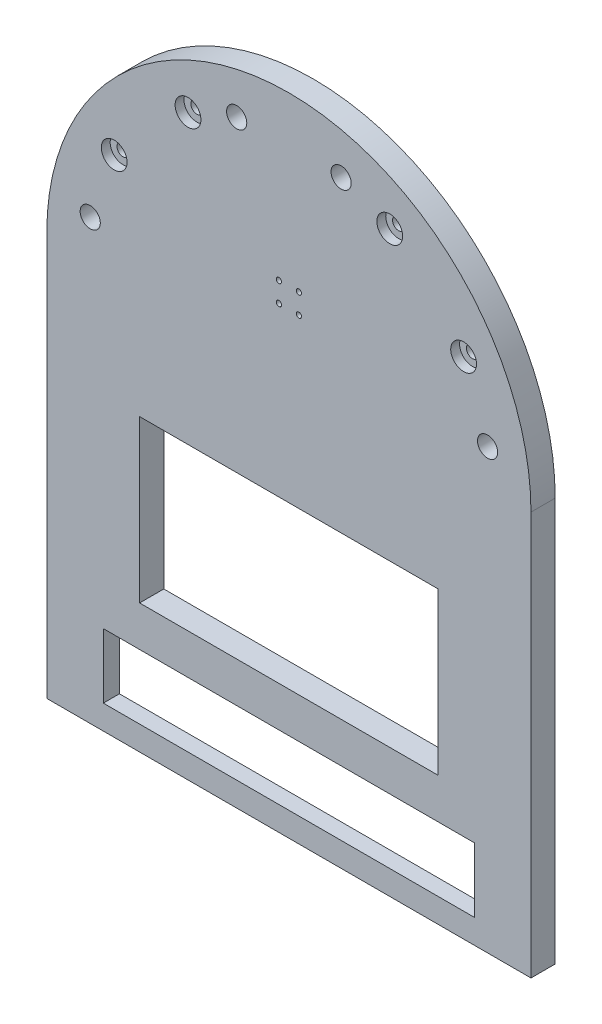
SolidWorks part; units mm, degrees
ref_plane "前视基准面" through (0, 0, 0) normal (0, 0, 1) x (1, 0, 0)
ref_plane "上视基准面" through (0, 0, 0) normal (0, 1, 0) x (1, 0, 0)
ref_plane "右视基准面" through (0, 0, 0) normal (1, 0, 0) x (0, 0, -1)
sketch "草图1" plane through (0, 0, 0) normal (0, 0, 1) x (1, 0, 0)
  line L0 (0, 0) -> (0, 283.2621) construction
  line L1 (0, 0) -> (-125, 216.5064) construction
  line L2 (0, 0) -> (-216.5064, 125) construction
  line L3 (-300, 0) -> (-300, -500)
  line L4 (-300, -500) -> (300, -500)
  line L5 (300, -500) -> (300, 0)
  arc A0 (300, 0) -> (-300, 0) centre (0, 0) ccw
  circle A1 centre (0, 0) radius 250 construction
  circle A2 centre (-216.5064, 125) radius 16
  circle A3 centre (-125, 216.5064) radius 16
  circle A4 centre (125, 216.5064) radius 16
  circle A5 centre (216.5064, 125) radius 16
  dimension "D1" = 300
  dimension "D2" = 500
  dimension "D5" = 32
  dimension "D6" = 32
  dimension "D7" = 500
  dimension "D3" = 30
  dimension "D4" = 30
extrude "凸台-拉伸1" add sketch "草图1" along normal blind 30
sketch "草图2" plane through (0, 0, 0) normal (0, 0, -1) x (-1, 0, 0)
  line L0 (0, 0) -> (0, 105.4108) construction
  circle A0 centre (-216.5064, 125) radius 18.5
  circle A1 centre (-125, 216.5064) radius 18.5
  circle A2 centre (-216.5064, 125) radius 22.5
  circle A3 centre (-125, 216.5064) radius 22.5
  circle A4 centre (216.5064, 125) radius 22.5
  circle A5 centre (216.5064, 125) radius 18.5
  circle A6 centre (125, 216.5064) radius 22.5
  circle A7 centre (125, 216.5064) radius 18.5
  dimension "D1" = 45
  dimension "D2" = 45
  dimension "D3" = 37
  dimension "D4" = 37
sketch "草图5" plane through (0, 0, 30) normal (0, 0, 1) x (1, 0, 0)
  line L1 (-185, -140) -> (185, -140)
  line L2 (-185, -140) -> (-185, -340)
  line L3 (-185, -340) -> (185, -340)
  line L4 (185, -140) -> (185, -340)
  line L5 (0, -340) -> (0, -140) construction
  line L6 (-185, -240) -> (185, -240) construction
  point P0 (0, -240)
  dimension "D1" = 200
  dimension "D2" = 370
  dimension "D3" = 240
extrude "切除-拉伸3" cut sketch "草图5" against normal through all
sketch "草图6" plane through (0, 0, 30) normal (0, 0, 1) x (1, 0, 0)
  line L1 (-230, -390) -> (230, -390)
  line L2 (-230, -390) -> (-230, -470)
  line L3 (-230, -470) -> (230, -470)
  line L4 (230, -390) -> (230, -470)
  line L5 (0, -470) -> (0, -390) construction
  line L6 (-230, -430) -> (230, -430) construction
  point P0 (0, -430)
  dimension "D1" = 80
  dimension "D2" = 460
  dimension "D3" = 430
extrude "切除-拉伸4" cut sketch "草图6" against normal blind 100
sketch "草图7" plane through (0, 0, 0) normal (0, 0, -1) x (-1, 0, 0)
  line L0 (230, -390) -> (230, -470) construction
  line L1 (-260, -360) -> (260, -360)
  line L2 (-260, -360) -> (-260, -500)
  line L3 (-260, -500) -> (260, -500)
  line L4 (260, -360) -> (260, -500)
  line L5 (0, -500) -> (0, -360) construction
  line L6 (-260, -430) -> (260, -430) construction
  line L7 (230, -470) -> (-230, -470) construction
  line L8 (-230, -390) -> (230, -390) construction
  line L9 (-230, -470) -> (-230, -390) construction
  point P0 (0, -430)
  dimension "D1" = 30
  dimension "D2" = 30
  dimension "D3" = 30
  dimension "D4" = 30
extrude "切除-拉伸5" cut sketch "草图7" against normal blind 10
sketch "草图8" plane through (0, 0, 30) normal (0, 0, 1) x (1, 0, 0)
  line L0 (0, 300) -> (0, -500)
  line L1 (-300, -500) -> (300, -500) construction
  arc A0 (300, 0) -> (-300, 0) centre (0, 0) ccw construction
  point P7 (0, 80)
  dimension "D1" = 80
sketch "草图10" plane through (0, 0, 30) normal (0, 0, 1) x (1, 0, 0)
  line L0 (0, 0) -> (-109.4264, 0) construction
  line L1 (0, 0) -> (0, 103.0554) construction
  line L2 (-246.2019, 43.412) -> (0, 0) construction
  line L3 (-64.7048, 241.4815) -> (0, 0) construction
  circle A0 centre (0, 0) radius 250 construction
  circle A1 centre (-246.2019, 43.412) radius 12.5
  circle A2 centre (-64.7048, 241.4815) radius 12.5
  circle A3 centre (246.2019, 43.412) radius 12.5
  circle A4 centre (64.7048, 241.4815) radius 12.5
  dimension "D1" = 500
  dimension "D4" = 25
  dimension "D5" = 25
  dimension "D2" = 10
  dimension "D3" = 15
extrude "切除-拉伸7" cut sketch "草图10" against normal blind 30
sketch "草图15" plane through (0, 0, 10) normal (0, 0, -1) x (-1, 0, 0)
  line L0 (260, -360) -> (-260, -360) construction
  line L1 (-230, -430) -> (-149.9927, -430) construction
  line L2 (-230, -470) -> (-230, -390) construction
  line L3 (0, 0) -> (0, -190.0619) construction
  line L4 (230, -430) -> (149.9927, -430) construction
  circle A0 centre (0, -370) radius 3
  circle A1 centre (-82, -370) radius 3
  circle A2 centre (-164, -370) radius 3
  circle A3 centre (-246, -370) radius 3
  circle A5 centre (-246, -490) radius 3
  circle A6 centre (-164, -490) radius 3
  circle A7 centre (-82, -490) radius 3
  circle A8 centre (0, -490) radius 3
  circle A9 centre (82, -490) radius 3
  circle A10 centre (164, -490) radius 3
  circle A11 centre (246, -490) radius 3
  circle A13 centre (246, -370) radius 3
  circle A14 centre (164, -370) radius 3
  circle A15 centre (82, -370) radius 3
  circle A16 centre (-246, -430) radius 3
  circle A17 centre (246, -430) radius 3
  dimension "D1" = 10
  dimension "D2" = 6
  dimension "D4" = 6
  dimension "D5" = 6
  dimension "D6" = 60
  dimension "D3" = 4
extrude "切除-拉伸12" cut sketch "草图15" against normal blind 10
sketch "草图16" plane through (0, 0, 0) normal (0, 0, -1) x (-1, 0, 0)
  line L0 (0, 0) -> (0, 120.0808) construction
  circle A0 centre (-216.5064, 125) radius 12.5
  circle A1 centre (-216.5064, 125) radius 18.5
  circle A2 centre (-125, 216.5064) radius 18.5
  circle A3 centre (-125, 216.5064) radius 12.5
  circle A4 centre (125, 216.5064) radius 12.5
  circle A5 centre (125, 216.5064) radius 18.5
  circle A6 centre (216.5064, 125) radius 18.5
  circle A7 centre (216.5064, 125) radius 12.5
  dimension "D1" = 25
  dimension "D2" = 25
extrude "凸台-拉伸2" add sketch "草图16" against normal blind 5
sketch "草图17" plane through (0, 0, 0) normal (0, 0, -1) x (-1, 0, 0)
  line L0 (0, 0) -> (0, 125) construction
  circle A0 centre (125, 216.5064) radius 7.55
  circle A1 centre (216.5064, 125) radius 7.55
  circle A2 centre (216.5064, 125) radius 16
  circle A3 centre (125, 216.5064) radius 16
  circle A4 centre (-125, 216.5064) radius 16
  circle A5 centre (-216.5064, 125) radius 16
  circle A6 centre (-216.5064, 125) radius 7.55
  circle A7 centre (-125, 216.5064) radius 7.55
  dimension "D1" = 15.1
  dimension "D2" = 15.1
  dimension "D3" = 32
  dimension "D4" = 32
extrude "凸台-拉伸4" add sketch "草图17" against normal offset from surface (19 mm away) 11 up to face at (-233.7019, 43.412, 30)
sketch "草图18" plane through (0, 0, 0) normal (0, 0, -1) x (-1, 0, 0)
  circle A5 centre (-246.2019, 43.412) radius 12.5
  circle A6 centre (-64.7048, 241.4815) radius 12.5
  circle A7 centre (64.7048, 241.4815) radius 12.5
  circle A8 centre (246.2019, 43.412) radius 12.5
extrude "凸台-拉伸5" add sketch "草图18" against normal blind 10
sketch "草图19" plane through (0, 0, 30) normal (0, 0, 1) x (1, 0, 0)
  line L1 (-12.375, 92.375) -> (12.375, 92.375) construction
  line L2 (-12.375, 92.375) -> (-12.375, 67.625) construction
  line L3 (-12.375, 67.625) -> (12.375, 67.625) construction
  line L4 (12.375, 92.375) -> (12.375, 67.625) construction
  line L5 (0, 67.625) -> (0, 92.375) construction
  line L6 (-12.375, 80) -> (12.375, 80) construction
  circle A0 centre (-12.375, 92.375) radius 3.25
  circle A1 centre (12.375, 92.375) radius 3.25
  circle A2 centre (-12.375, 67.625) radius 3.25
  circle A3 centre (12.375, 67.625) radius 3.25
  point P0 (0, 80)
  dimension "D3" = 6.5
  dimension "D1" = 24.75
  dimension "D2" = 80
extrude "切除-拉伸13" cut sketch "草图19" against normal blind 10
